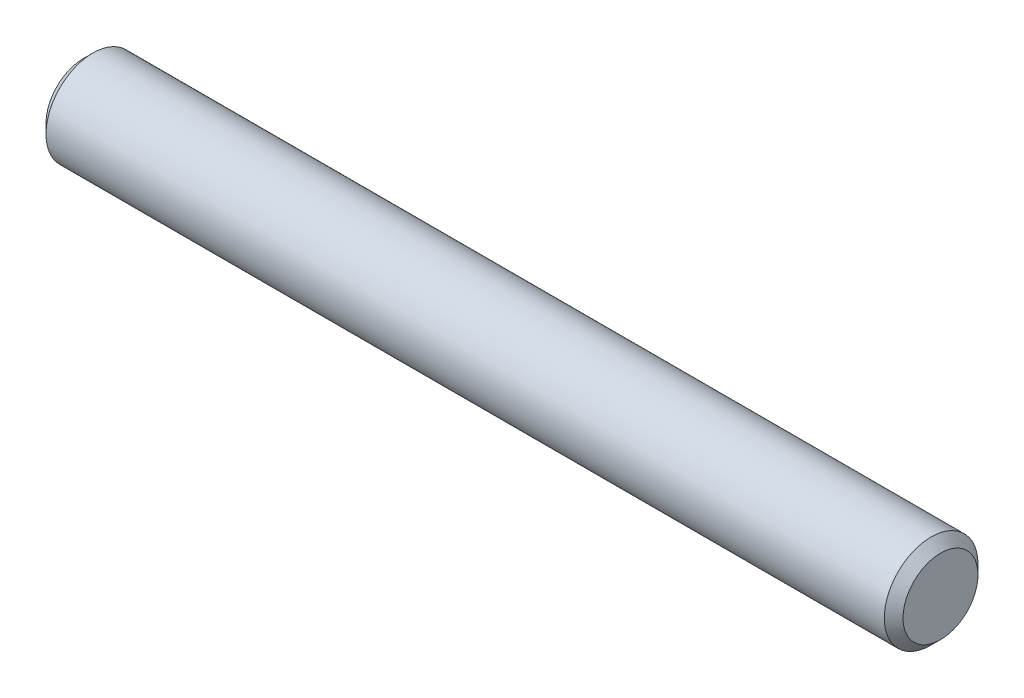
SolidWorks part; units mm, degrees
material "AISI 316 Stainless Steel Sheet (SS)"
ref_plane "Front" through (0, 0, 0) normal (0, 0, 1) x (1, 0, 0)
ref_plane "Top" through (0, 0, 0) normal (0, 1, 0) x (1, 0, 0)
ref_plane "Right" through (0, 0, 0) normal (1, 0, 0) x (0, 0, -1)
sketch "Sketch1" plane through (0, 0, 0) normal (0, 0, 1) x (1, 0, 0)
  line L0 (-12.7, 0) -> (12.7, 0) construction
  line L1 (12.7, 1.3891) -> (12.7, -1.3891) construction
  line L2 (-12.7, 1.3891) -> (-12.7, -1.3891) construction
  dimension "Length" = 25.4
  dimension "Diameter" = 2.7781
sketch "Sketch2" plane through (0, 0, 0) normal (1, 0, 0) x (0, 0, -1)
  circle A0 centre (0, 0) radius 1.3891
extrude "Extrude1" add sketch "Sketch2" against normal up to vertex (12.7 mm away) and the other way up to vertex (12.7 mm away) up to point (-12.7, 1.3891, 0) other way up to point (12.7, 1.3891, 0)
chamfer "Chamfer1" distance 0.2778 angle 45 2 edges at (12.7, 0, -1.3891) (-12.7, 0, -1.3891)
equation "\"D1@Chamfer1\" = \"Diameter@Sketch1\"*.1"
